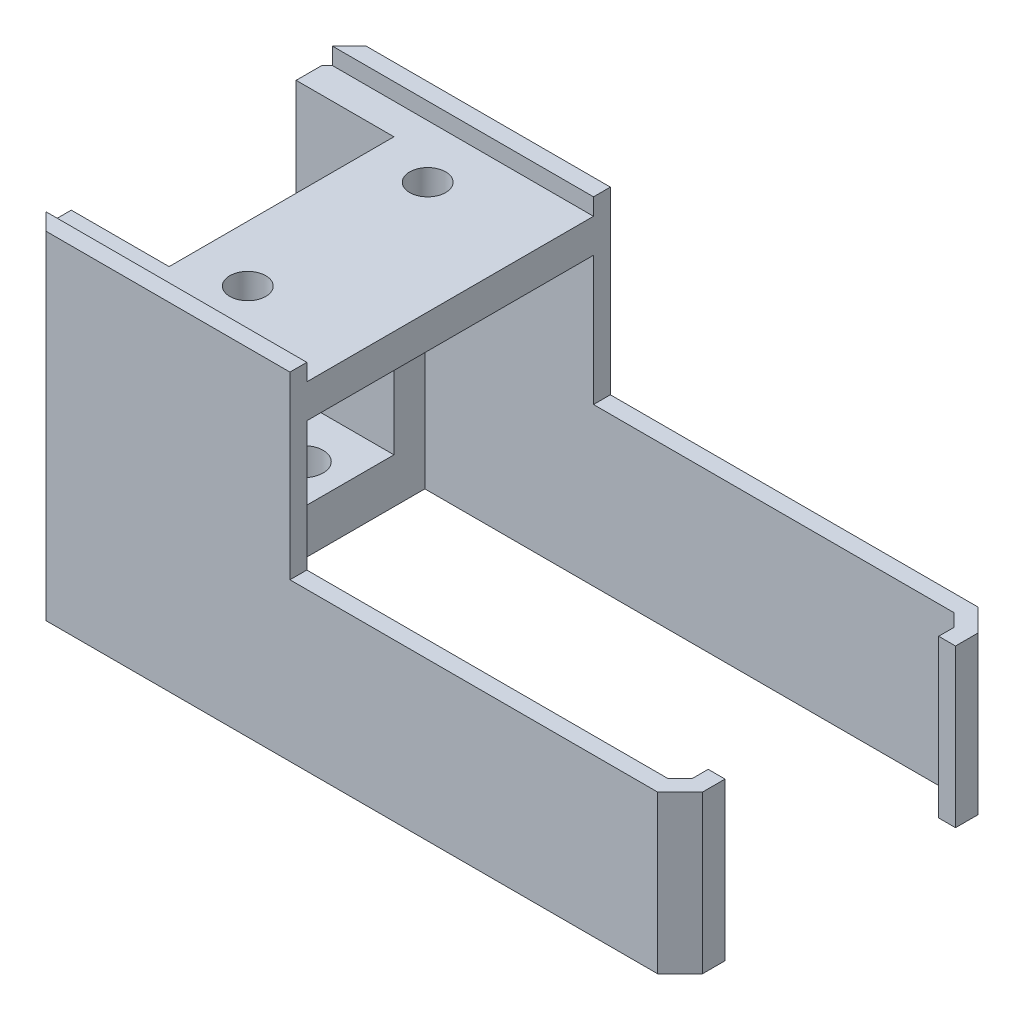
SolidWorks part; units mm, degrees
material "ABS"
ref_plane "Płaszczyzna przednia" through (0, 0, 0) normal (0, 0, 1) x (1, 0, 0)
ref_plane "Płaszczyzna górna" through (0, 0, 0) normal (0, 1, 0) x (1, 0, 0)
ref_plane "Płaszczyzna prawa" through (0, 0, 0) normal (1, 0, 0) x (0, 0, -1)
sketch "Szkic1" plane through (0, 0, 0) normal (0, 1, 0) x (1, 0, 0)
  line L0 (-88.6255, 0) -> (0, 0) construction
  line L1 (-39.7, 10) -> (-31, 10)
  line L2 (-39.7, 10) -> (-39.7, 1)
  line L3 (-39.7, 1) -> (-31, 1)
  line L4 (-31, 10) -> (-31, 1)
  line L5 (-39.7, -1) -> (-31, -1)
  line L6 (-39.7, -1) -> (-39.7, -10)
  line L7 (-39.7, -10) -> (-31, -10)
  line L8 (-31, -1) -> (-31, -10)
  line L9 (-55, 0) -> (55, 0) construction
  line L10 (0, -55) -> (0, 55) construction
  circle A0 centre (-34.5, 5.45) radius 1.75
  circle A2 centre (-34.5, -5.45) radius 1.75
  dimension "D4" = 3.5
  dimension "D5" = 3.5
  dimension "D6" = 5.45
  dimension "D1" = 20
  dimension "D2" = 39.7
  dimension "D3" = 31
  dimension "2" = 2
extrude "Dodanie-wyciągnięcie1" add sketch "Szkic1" along normal blind 2
sketch "Szkic2" plane through (0, 2, 0) normal (0, 1, 0) x (1, 0, 0)
  line L1 (-39.7, 10) -> (-31, 10)
  line L2 (-39.7, 10) -> (-39.7, -10)
  line L3 (-39.7, -10) -> (-31, -10)
  line L4 (-31, 10) -> (-31, -10)
  circle A0 centre (-34.5, 5.45) radius 1.75
  circle A1 centre (-34.5, 5.45) radius 1.75 construction
  circle A2 centre (-34.5, -5.45) radius 1.75
  circle A3 centre (-34.5, -5.45) radius 1.75 construction
extrude "Dodanie-wyciągnięcie2" add sketch "Szkic2" along normal blind 2
ref_plane "Płaszczyzna1" through (0, 0, 0) normal (0, -1, 0) x (-1, 0, 0)
sketch "Szkic5" plane through (0, 0, 0) normal (0, -1, 0) x (-1, 0, 0)
  line L0 (39.7, -10) -> (39.7, -12.25)
  line L1 (39.7, -12.25) -> (37.7, -14.25)
  line L2 (37.7, -14.25) -> (-16.7, -14.25)
  line L3 (-16.7, -14.25) -> (-18.7, -12.25)
  line L4 (-18.7, -12.25) -> (-18.7, -10.25)
  line L5 (-18.7, -10.25) -> (31, -10.25)
  line L6 (31, -10.25) -> (31, -10)
  line L7 (-55, 0) -> (55, 0) construction
  line L9 (39.7, -10) -> (31, -10)
  line L10 (39.7, 10) -> (39.7, 12.25)
  line L11 (39.7, 12.25) -> (37.7, 14.25)
  line L12 (37.7, 14.25) -> (-16.7, 14.25)
  line L13 (-16.7, 14.25) -> (-18.7, 12.25)
  line L14 (-18.7, 12.25) -> (-18.7, 10.25)
  line L15 (-18.7, 10.25) -> (31, 10.25)
  line L16 (31, 10.25) -> (31, 10)
  line L17 (39.7, 10) -> (31, 10)
  dimension "D1" = 14.25
  dimension "D2" = 4
  dimension "D3" = 135
  dimension "D4" = 2
  dimension "D5" = 58.4
extrude "Dodanie-wyciągnięcie3" add sketch "Szkic5" against normal blind 14
sketch "Szkic7" plane through (0, 14, 0) normal (0, 1, 0) x (1, 0, 0)
  line L0 (-31, 10.25) -> (17.2, 10.25)
  line L1 (18.7, 10.25) -> (-31, 10.25) construction
  line L2 (17.2, 10.25) -> (17.2, 11.6287)
  line L3 (17.2, 11.6287) -> (16.0787, 12.75)
  line L4 (16.0787, 12.75) -> (-31, 12.75)
  line L5 (-31, 12.75) -> (-31, 10.25)
  line L6 (18.7, 12.25) -> (18.7, 10.25) construction
  line L7 (16.7, 14.25) -> (18.7, 12.25) construction
  line L8 (-37.7, 14.25) -> (16.7, 14.25) construction
  line L9 (-55, 0) -> (55, 0) construction
  line L10 (16.0787, -12.75) -> (-31, -12.75)
  line L11 (17.2, -11.6287) -> (16.0787, -12.75)
  line L12 (17.2, -10.25) -> (17.2, -11.6287)
  line L13 (-31, -10.25) -> (17.2, -10.25)
  line L14 (-31, -12.75) -> (-31, -10.25)
  dimension "D1" = 1.5
  dimension "D2" = 1.5
  dimension "D3" = 1.5
extrude "Wytnij-wyciągnięcie1" cut sketch "Szkic7" against normal up to next
sketch "Szkic8" plane through (0, 14, 0) normal (0, 1, 0) x (1, 0, 0)
  line L0 (-31, 10) -> (-39.7, 10)
  line L1 (-39.7, 10) -> (-39.7, 12.25)
  line L2 (-39.7, 10) -> (-39.7, 12.25) construction
  line L3 (-39.7, 12.25) -> (-37.7, 14.25) construction
  line L4 (-39.7, 12.25) -> (-37.7, 14.25)
  line L5 (-37.7, 14.25) -> (-16, 14.25)
  line L6 (-37.7, 14.25) -> (16.7, 14.25) construction
  line L7 (-16, 14.25) -> (-16, 12.75)
  line L8 (16.0787, 12.75) -> (-31, 12.75) construction
  line L9 (-16, 12.75) -> (-31, 12.75)
  line L10 (-31, 12.75) -> (-31, 10)
  line L11 (-55, 0) -> (55, 0) construction
  line L12 (-16, -12.75) -> (-31, -12.75)
  line L13 (-16, -14.25) -> (-16, -12.75)
  line L14 (-37.7, -14.25) -> (-16, -14.25)
  line L15 (-39.7, -12.25) -> (-37.7, -14.25)
  line L16 (-39.7, -10) -> (-39.7, -12.25)
  line L17 (-31, -10) -> (-39.7, -10)
  line L18 (-31, -12.75) -> (-31, -10)
  dimension "D1" = 15
extrude "Dodanie-wyciągnięcie7" add sketch "Szkic8" along normal offset from surface (14.5 mm away) 28.5 up to face at (-6.7747, 0, -10.239)
sketch "Szkic10" plane through (0, 28.5, 0) normal (0, 1, 0) x (1, 0, 0)
  line L0 (-55, 0) -> (55, 0) construction
  line L1 (-31, 12.75) -> (-16, 12.75)
  line L2 (-31, 12.75) -> (-31, -12.75)
  line L3 (-31, -12.75) -> (-16, -12.75)
  line L4 (-16, 12.75) -> (-16, -12.75)
  circle A0 centre (-26, 8) radius 1.6
  circle A1 centre (-26, -8) radius 1.6
  dimension "D1" = 3.2
  dimension "D2" = 8
  dimension "5" = 5
extrude "Dodanie-wyciągnięcie9" add sketch "Szkic10" against normal blind 3
sketch "Szkic11" plane through (0, 28.5, 0) normal (0, 1, 0) x (1, 0, 0)
  line L0 (-16, 12.75) -> (-16, 14.25)
  line L1 (-16, 14.25) -> (-37.7, 14.25)
  line L2 (-37.7, 14.25) -> (-39.2, 12.75)
  line L3 (-37.7, 14.25) -> (-39.7, 12.25) construction
  line L4 (-39.2, 12.75) -> (-16, 12.75)
  line L5 (-55, 0) -> (55, 0) construction
  line L6 (-37.7, -14.25) -> (-39.2, -12.75)
  line L7 (-16, -14.25) -> (-37.7, -14.25)
  line L8 (-16, -12.75) -> (-16, -14.25)
  line L9 (-39.2, -12.75) -> (-16, -12.75)
extrude "Dodanie-wyciągnięcie10" add sketch "Szkic11" along normal blind 1.5
